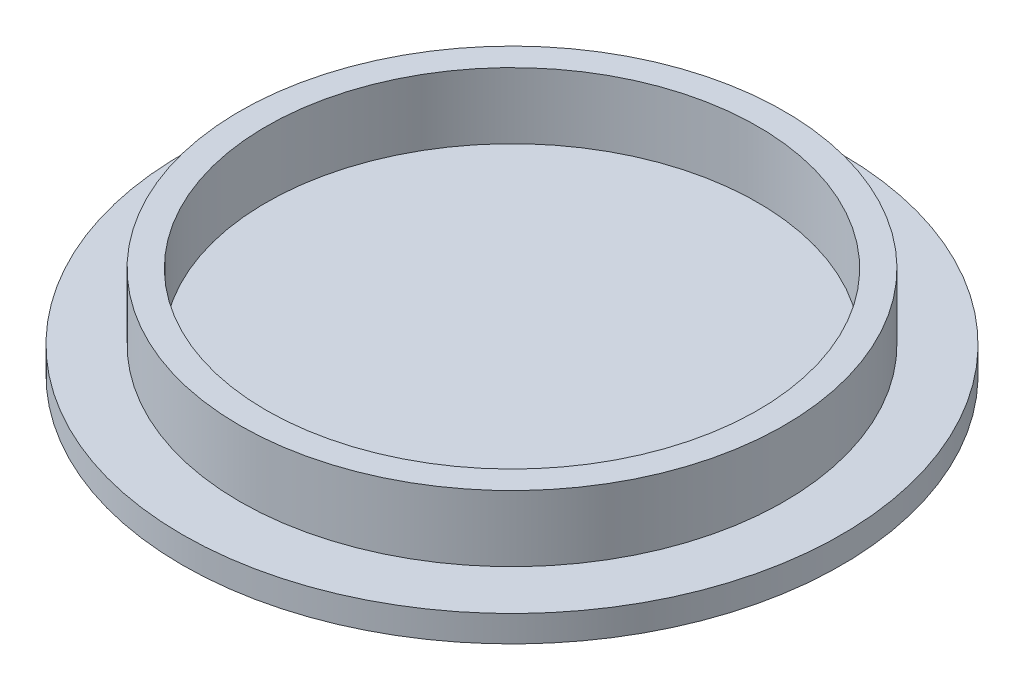
SolidWorks part; units mm, degrees
ref_plane "Front Plane" through (0, 0, 0) normal (0, 0, 1) x (1, 0, 0)
ref_plane "Top Plane" through (0, 0, 0) normal (0, 1, 0) x (1, 0, 0)
ref_plane "Right Plane" through (0, 0, 0) normal (1, 0, 0) x (0, 0, -1)
other "Bounding Box"
ref_plane "Default Plane" through (-8.9266, -12.7485, 0) normal (-0.1736, 0.9848, 0) x (0.9848, 0.1736, 0)
sketch "Sketch1" plane through (0, 0, 0) normal (0, 1, 0) x (1, 0, 0)
  circle A0 centre (0, 0) radius 63.5
  dimension "D1" = 127
extrude "Boss-Extrude1" add sketch "Sketch1" along normal blind 5.08
sketch "Sketch2" plane through (0, 5.08, 0) normal (0, 1, 0) x (1, 0, 0)
  circle A0 centre (0, 0) radius 52.451
  circle A1 centre (0, 0) radius 47.371
  dimension "D1" = 5.08
  dimension "D2" = 104.902
extrude "Boss-Extrude2" add sketch "Sketch2" along normal blind 12.7
